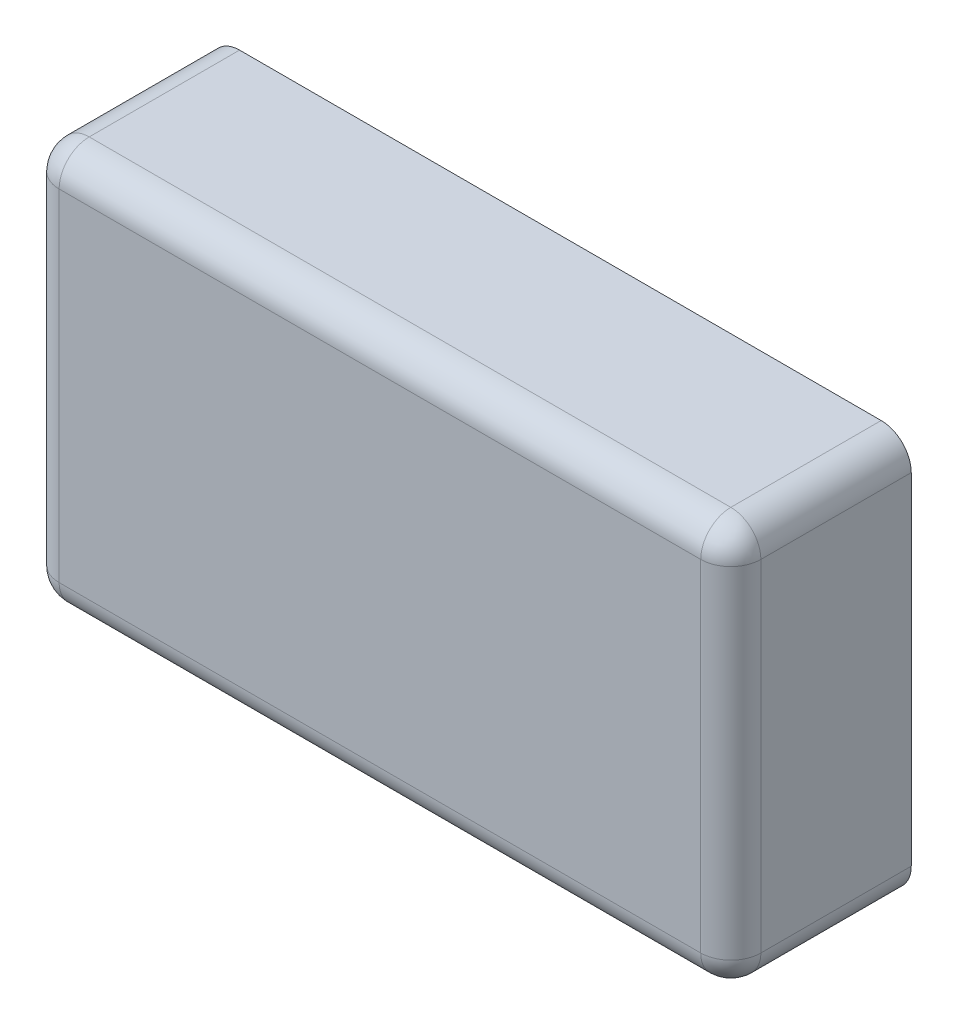
SolidWorks part; units mm, degrees
material "60a Breaker"
ref_plane "Front Plane" through (0, 0, 0) normal (0, 0, 1) x (1, 0, 0)
ref_plane "Top Plane" through (0, 0, 0) normal (0, 1, 0) x (1, 0, 0)
ref_plane "Right Plane" through (0, 0, 0) normal (1, 0, 0) x (0, 0, -1)
sketch "Sketch1" plane through (0, 0, 0) normal (0, 0, 1) x (1, 0, 0)
  line L0 (-16.8402, 70) -> (-73.8402, 43) construction
  line L1 (-10.3402, 76.5) -> (-80.3402, 76.5)
  line L2 (-10.3402, 76.5) -> (-10.3402, 36.5)
  line L3 (-10.3402, 36.5) -> (-80.3402, 36.5)
  line L4 (-80.3402, 76.5) -> (-80.3402, 36.5)
  line L5 (-73.8402, 43) -> (-73.8402, 70) construction
  line L6 (-73.8402, 70) -> (-16.8402, 70) construction
  point P8 (-45.3402, 56.5)
  point P10 (-45.3402, 36.5)
  point P11 (-80.3402, 56.5)
  dimension "D1" = 70
  dimension "D2" = 40
extrude "Boss-Extrude1" add sketch "Sketch1" along normal blind 18
fillet "Fillet1" radius 3 8 edges at (-45.3402, 36.5, 18) (-80.3402, 56.5, 18) (-45.3402, 76.5, 18) (-10.3402, 56.5, 18) (-10.3402, 76.5, 9) (-80.3402, 76.5, 9) (-80.3402, 36.5, 9) (-10.3402, 36.5, 9)
ref_plane "Plane1" through (-45.3402, 0, 0) normal (1, 0, 0) x (0, 0, -1)
